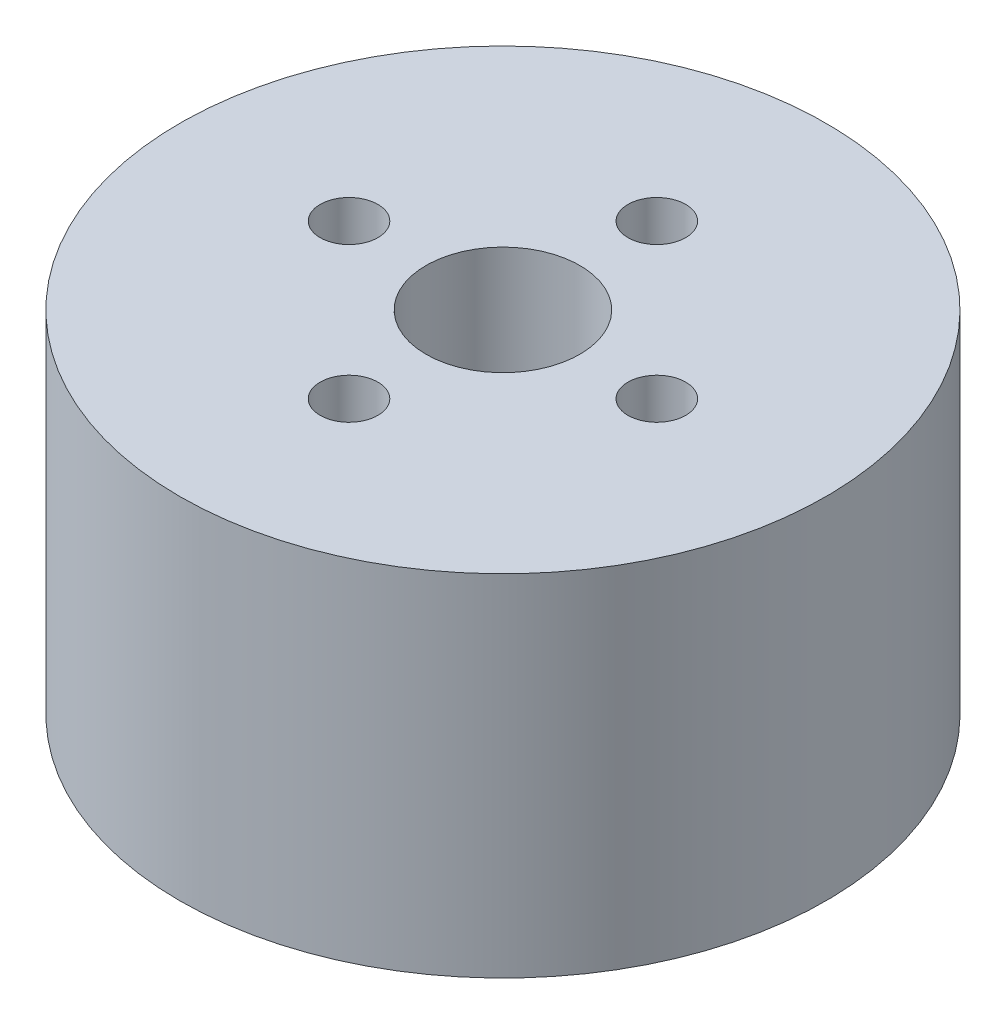
SolidWorks part; units mm, degrees
ref_plane "前视基准面" through (0, 0, 0) normal (0, 0, 1) x (1, 0, 0)
ref_plane "上视基准面" through (0, 0, 0) normal (0, 1, 0) x (1, 0, 0)
ref_plane "右视基准面" through (0, 0, 0) normal (1, 0, 0) x (0, 0, -1)
sketch "Sketch1" plane through (0, 0, 0) normal (0, 1, 0) x (1, 0, 0)
  circle A0 centre (0, 0) radius 16.8
  dimension "D1" = 33.6
extrude "Boss-Extrude1" add sketch "Sketch1" along normal blind 18.2
sketch "Sketch2" plane through (0, 18.2, 0) normal (0, 1, 0) x (1, 0, 0)
  circle A0 centre (0, 0) radius 4
  dimension "D1" = 8
extrude "Cut-Extrude1" cut sketch "Sketch2" against normal through all
sketch "Sketch3" plane through (0, 18.2, 0) normal (0, 1, 0) x (1, 0, 0)
  circle A0 centre (0, 8) radius 1.5
  circle A1 centre (8, 0) radius 1.5
  circle A2 centre (0, -8) radius 1.5
  circle A3 centre (-8, 0) radius 1.5
  point P12 (0, 0)
  dimension "D1" = 3
  dimension "D2" = 8
  dimension "D3" = 4
extrude "Cut-Extrude2" cut sketch "Sketch3" against normal blind 5
sketch "Sketch4" plane through (0, 0, 0) normal (0, -1, 0) x (1, 0, 0)
  circle A0 centre (0, 11.25) radius 1.5
  circle A1 centre (11.25, 0) radius 1.5
  circle A2 centre (0, -11.25) radius 1.5
  circle A3 centre (-11.25, 0) radius 1.5
  point P12 (0, 0)
  dimension "D1" = 11.25
  dimension "D2" = 3
  dimension "D3" = 4
extrude "Cut-Extrude3" cut sketch "Sketch4" against normal blind 5
